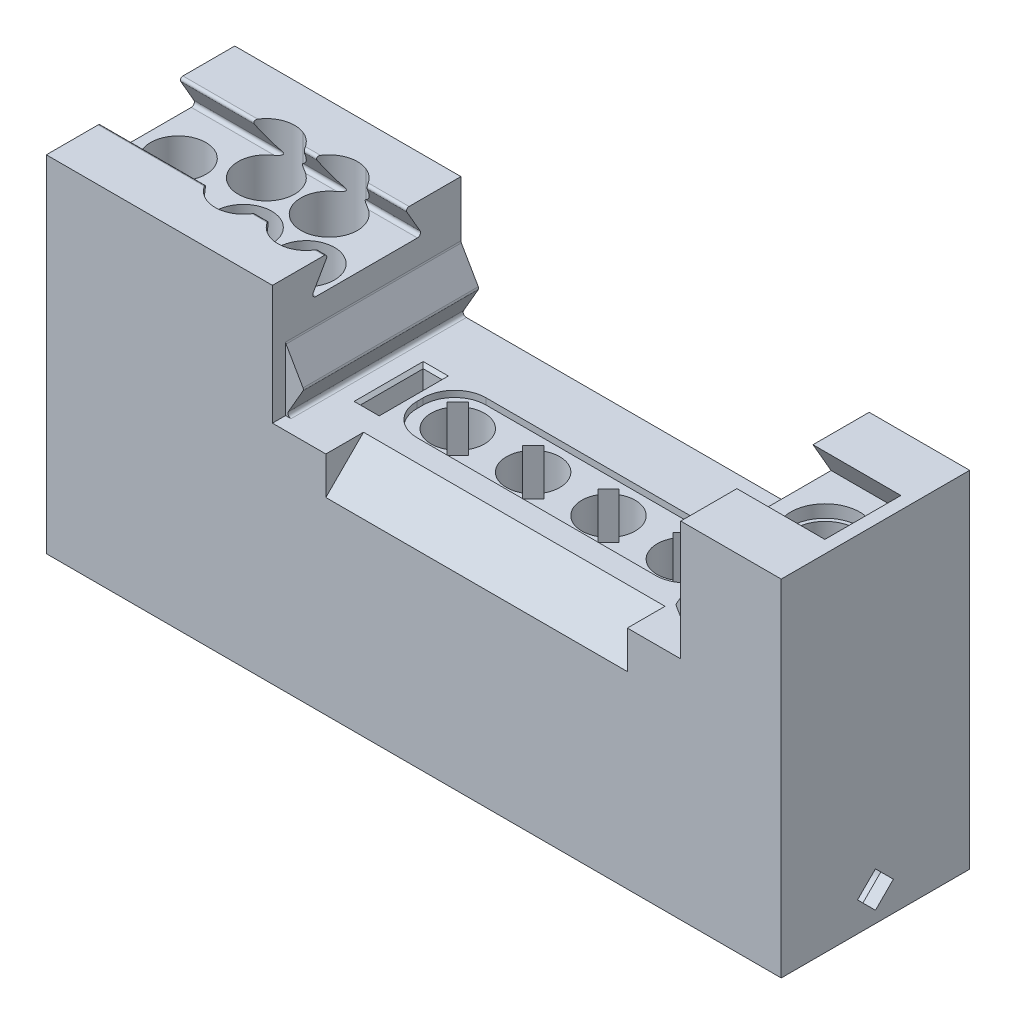
SolidWorks part; units mm, degrees
ref_plane "Front Plane" through (0, 0, 0) normal (0, 0, 1) x (1, 0, 0)
ref_plane "Top Plane" through (0, 0, 0) normal (0, 1, 0) x (1, 0, 0)
ref_plane "Right Plane" through (0, 0, 0) normal (1, 0, 0) x (0, 0, -1)
sketch "Sketch1" plane through (0, 0, 0) normal (0, 1, 0) x (1, 0, 0)
  line L1 (57.5, -15) -> (-57.5, -15)
  line L2 (57.5, -15) -> (57.5, 15)
  line L3 (57.5, 15) -> (-57.5, 15)
  line L4 (-57.5, -15) -> (-57.5, 15)
  line L5 (57.5, -15) -> (-57.5, 15) construction
  line L6 (57.5, 15) -> (-57.5, -15) construction
  point P0 (0, 0)
  dimension "D1" = 30
  dimension "D2" = 115
extrude "Boss-Extrude1" add sketch "Sketch1" along normal mid plane 55
sketch "Sketch2" plane through (0, 0, 0) normal (1, 0, 0) x (0, 0, -1)
  line L0 (0, 27.5) -> (0, 22.5) construction
  line L2 (-15, 27.5) -> (15, 27.5) construction
  line L3 (-6.0566, 27.5) -> (-8.9434, 22.5)
  line L4 (6.0566, 27.5) -> (8.9434, 22.5)
  line L5 (-8.9434, 22.5) -> (8.9434, 22.5)
  line L6 (-8.9434, 22.5) -> (-15, 22.5) construction
  line L7 (-15, 27.5) -> (-15, -27.5) construction
  line L8 (8.9434, 22.5) -> (15, 22.5) construction
  line L9 (-6.0566, 27.5) -> (0, 27.5)
  line L10 (0, 27.5) -> (6.0566, 27.5)
  dimension "D1" = 5
  dimension "D2" = 30
extrude "Cut-Extrude1" cut sketch "Sketch2" against normal through all both and the other way through all
sketch "Sketch5" plane through (0, 22.5, 0) normal (0, 1, 0) x (1, 0, 0)
  line L0 (-51.5, 0) -> (0, 0) construction
  line L1 (-57.5, -8.9434) -> (-57.5, 8.9434) construction
  circle A0 centre (-51.5, 0) radius 4.4
  dimension "D2" = 8.8
  dimension "D1" = 6
extrude "Cut-Extrude3" cut sketch "Sketch5" against normal blind 8
sketch "Sketch3" plane through (0, 22.5, 0) normal (0, 1, 0) x (1, 0, 0)
  line L0 (0, 0) -> (51.5, 0) construction
  line L1 (57.5, -8.9434) -> (57.5, 8.9434) construction
  circle A0 centre (51.5, 0) radius 4.9
  dimension "D1" = 9.8
  dimension "D2" = 6
extrude "Cut-Extrude2" cut sketch "Sketch3" against normal blind 24
sketch "Sketch6" plane through (0, 14.5, 0) normal (0, 1, 0) x (1, 0, 0)
  circle A0 centre (-51.5, 0) radius 3.1
  dimension "D1" = 6.2
extrude "Cut-Extrude4" cut sketch "Sketch6" against normal blind 6
sketch "Sketch7" plane through (0, 22.5, 0) normal (0, 1, 0) x (1, 0, 0)
  circle A0 centre (51.5, 0) radius 5.5
  dimension "D1" = 11
extrude "Cut-Extrude5" cut sketch "Sketch7" against normal blind 2
sketch "Sketch10" plane through (0, 0, 0) normal (0, 0, 1) x (1, 0, 0)
  line L0 (11, 27.5) -> (11, 8.5) construction
  line L1 (-57.5, 27.5) -> (57.5, 27.5) construction
  line L2 (-21.5, 27.5) -> (-21.5, 18.5)
  line L3 (43.5, 27.5) -> (43.5, 18.5)
  line L4 (-21.5, 18.5) -> (-18.6132, 13.5)
  line L5 (43.5, 18.5) -> (40.6132, 13.5)
  line L6 (-18.6132, 13.5) -> (-21.5, 8.5)
  line L7 (40.6132, 13.5) -> (43.5, 8.5)
  line L8 (-21.5, 8.5) -> (43.5, 8.5)
  line L9 (-21.5, 27.5) -> (43.5, 27.5)
  dimension "D1" = 19
  dimension "D2" = 60
  dimension "D3" = 65
  dimension "D4" = 11
  dimension "D5" = 5
extrude "Cut-Extrude7" cut sketch "Sketch10" against normal through all both and the other way through all
fillet "Fillet2" radius 0.4 4 edges at (-39.5, 27.5, 6.0566) (-39.5, 27.5, -6.0566) (40.6132, 13.5, 0) (-18.6132, 13.5, 0)
fillet "Fillet1" radius 0.5 6 edges at (-39.5, 22.5, 8.9434) (-39.5, 22.5, -8.9434) (-21.5, 18.5, 0) (-21.5, 8.5, 0) (43.5, 18.5, 0) (43.5, 8.5, 0)
sketch "Sketch13" plane through (57.5, 0, 0) normal (1, 0, 0) x (0, 0, -1)
  line L1 (-15, 27.5) -> (15, 27.5)
  line L2 (-15, 27.5) -> (-15, -27.5)
  line L3 (-15, -27.5) -> (15, -27.5)
  line L4 (15, 27.5) -> (15, -27.5)
extrude "Boss-Extrude2" add sketch "Sketch13" along normal blind 2
sketch "Sketch16" plane through (-57.5, 0, 0) normal (-1, 0, 0) x (0, 0, 1)
  line L0 (0, -27.5) -> (0, -7.5) construction
  line L9 (-15, -27.5) -> (15, -27.5) construction
  line L10 (-11, -27.5) -> (-11, -12.5) construction
  line L11 (11, -27.5) -> (11, -12.5) construction
  line L12 (-11, -12.5) -> (-11, -7.5)
  line L13 (11, -12.5) -> (11, -7.5)
  line L14 (-11, -7.5) -> (-2, 1.5)
  line L15 (11, -7.5) -> (2, 1.5)
  line L16 (-2, 1.5) -> (2, 1.5)
  line L17 (-11, -12.5) -> (11, -12.5)
  line L18 (-15, 27.5) -> (-15, -27.5) construction
  dimension "D1" = 4
  dimension "D2" = 15
  dimension "D3" = 135
  dimension "D4" = 4
  dimension "D5" = 5
extrude "Cut-Extrude10" cut sketch "Sketch16" against normal blind 35
sketch "Sketch17" plane through (-57.5, 0, 0) normal (-1, 0, 0) x (0, 0, 1)
  line L0 (-15, -27.5) -> (15, -27.5) construction
  line L1 (-11, -12.5) -> (11, -12.5)
  line L2 (-11, -12.5) -> (-11, -27.5)
  line L3 (-11, -27.5) -> (11, -27.5)
  line L4 (11, -12.5) -> (11, -27.5)
  line L5 (11, -12.5) -> (11, -7.5) construction
extrude "Cut-Extrude11" cut sketch "Sketch17" against normal blind 2
fillet "Fillet6" radius 2 4 edges at (-40, -7.5, 11) (-40, 1.5, 2) (-40, 1.5, -2) (-40, -7.5, -11)
sketch "Sketch18" plane through (-57.5, 0, 0) normal (-1, 0, 0) x (0, 0, 1)
  line L21 (-13, -27.5) -> (13, -27.5)
  line L26 (13, -27.5) -> (13, -8.3284)
  line L27 (11.8284, -5.5) -> (4, 2.3284)
  line L28 (1.1716, 3.5) -> (-1.1716, 3.5)
  line L29 (-4, 2.3284) -> (-11.8284, -5.5)
  line L30 (-13, -8.3284) -> (-13, -27.5)
  line L31 (13, -27.5) -> (13, -8.3284)
  line L32 (11.8284, -5.5) -> (4, 2.3284)
  line L33 (1.1716, 3.5) -> (-1.1716, 3.5)
  line L34 (-4, 2.3284) -> (-11.8284, -5.5)
  line L35 (-13, -8.3284) -> (-13, -27.5)
  arc A8 (13, -8.3284) -> (11.8284, -5.5) centre (9, -8.3284) ccw
  arc A9 (4, 2.3284) -> (1.1716, 3.5) centre (1.1716, -0.5) ccw
  arc A10 (-1.1716, 3.5) -> (-4, 2.3284) centre (-1.1716, -0.5) ccw
  arc A11 (-11.8284, -5.5) -> (-13, -8.3284) centre (-9, -8.3284) ccw
  arc A12 (13, -8.3284) -> (11.8284, -5.5) centre (9, -8.3284) ccw
  arc A13 (4, 2.3284) -> (1.1716, 3.5) centre (1.1716, -0.5) ccw
  arc A14 (-1.1716, 3.5) -> (-4, 2.3284) centre (-1.1716, -0.5) ccw
  arc A15 (-11.8284, -5.5) -> (-13, -8.3284) centre (-9, -8.3284) ccw
  dimension "D1" = 2
extrude "Cut-Extrude13" cut sketch "Sketch18" against normal blind 1 from offset 1 offset against normal yes
sketch "Sketch19" plane through (-55.5, 0, 0) normal (-1, 0, 0) x (0, 0, 1)
  line L0 (0, -27.5) -> (0, -12.5) construction
  line L5 (5.6569, -20) -> (0, -14.3431)
  line L6 (5.6569, -20) -> (0, -25.6569)
  line L7 (-13, -27.5) -> (13, -27.5) construction
  line L8 (11, -12.5) -> (-11, -12.5) construction
  line L9 (0, -14.3431) -> (-5.6569, -20)
  line L10 (0, -25.6569) -> (-5.6569, -20)
  line L11 (5.6569, -20) -> (-5.6569, -20) construction
  line L12 (0, -14.3431) -> (0, -25.6569) construction
  line L21 (0, -23.5355) -> (-3.5355, -20) construction
  line L22 (0, -23.5355) -> (3.5355, -20) construction
  line L23 (-3.5355, -20) -> (0, -16.4645) construction
  line L24 (3.5355, -20) -> (0, -16.4645) construction
  line L25 (0, -23.5355) -> (0, -16.4645) construction
  line L26 (-3.5355, -20) -> (3.5355, -20) construction
  point P1 (0, -20)
  point P2 (0, -20)
  point P11 (0, -20)
  dimension "D2" = 8
  dimension "D1" = 5
extrude "Cut-Extrude14" cut sketch "Sketch19" against normal offset from surface (105 mm away) 10 up to face at (59.5, 0, 0)
sketch "Sketch21" plane through (59.5, 0, 0) normal (1, 0, 0) x (0, 0, -1)
  line L0 (0, -25.6569) -> (-5.6569, -20) construction
  line L1 (5.6569, -20) -> (0, -25.6569) construction
  line L2 (0, -25.6569) -> (-5.6569, -20) construction
  line L3 (5.6569, -20) -> (0, -25.6569) construction
  line L20 (5.4801, -19.8232) -> (0, -25.3033) construction
  line L21 (0, -25.3033) -> (-5.4801, -19.8232) construction
  line L22 (0, -25.3033) -> (-2.5, -22.8033) construction
  line L23 (0, -25.3033) -> (2.5, -22.8033) construction
  line L24 (-2.5, -22.8033) -> (0, -20.3033) construction
  line L25 (2.5, -22.8033) -> (0, -20.3033) construction
  circle A0 centre (0, -22.8033) radius 2.5 construction
  circle A1 centre (0, -22.8033) radius 3.75
  dimension "D2" = 5
  dimension "D3" = 7.5
  dimension "D1" = 0.25
extrude "Cut-Extrude15" cut sketch "Sketch21" against normal blind 30 from offset 2 offset against normal yes
sketch "Sketch29" plane through (59.5, 0, 0) normal (1, 0, 0) x (0, 0, -1)
  line L0 (0, -25.3033) -> (-5.4801, -19.8232) construction
  line L1 (2.5, -22.8033) -> (0, -20.3033) construction
  line L2 (-2.5, -22.8033) -> (0, -20.3033) construction
  line L3 (0, -25.3033) -> (-2.5, -22.8033) construction
  line L12 (2.5, -22.8033) -> (0, -20.3033) construction
  line L13 (-2.5, -22.8033) -> (0, -20.3033) construction
  line L14 (0, -25.6569) -> (-2.8536, -22.8033)
  line L15 (5.4801, -19.8232) -> (0, -25.3033) construction
  line L16 (2.5, -22.8033) -> (0, -25.3033) construction
  line L17 (-2.8536, -22.8033) -> (0, -19.9497)
  line L18 (2.8536, -22.8033) -> (0, -19.9497)
  line L19 (2.8536, -22.8033) -> (0, -25.6569)
  dimension "D2" = 0.25
extrude "Cut-Extrude23" cut sketch "Sketch29" against normal up to next
sketch "Sketch23" plane through (0, 0, 15) normal (0, 0, 1) x (1, 0, 0)
  line L0 (-21.5, 18.634) -> (-21.5, 8.5)
  line L1 (-21.5, 8.5) -> (-20.634, 8.5)
  line L2 (-20.634, 8.5) -> (42.634, 8.5)
  line L5 (43.5, 18.634) -> (-21.5, 18.634)
  line L6 (42.634, 8.5) -> (43.5, 8.5)
  line L7 (43.5, 8.5) -> (43.5, 18.634)
extrude "Cut-Extrude17" cut sketch "Sketch23" against normal blind 2.1
sketch "Sketch24" plane through (0, 8.5, 0) normal (0, 1, 0) x (1, 0, 0)
  line L0 (11, 15) -> (11, -15) construction
  line L1 (-20.634, 15) -> (42.634, 15) construction
  line L2 (-21.5, -15) -> (43.5, -15) construction
  line L3 (-7, 0) -> (5, 0) construction
  line L4 (49.5, 0) -> (-55.5, 0) construction
  line L5 (29, 0) -> (17, 0) construction
  line L6 (5, 0) -> (17, 0) construction
  circle A0 centre (-7, 0) radius 4.25
  circle A1 centre (29, 0) radius 4.25
  circle A2 centre (5, 0) radius 4.25
  circle A3 centre (17, 0) radius 4.25
  dimension "D2" = 8.5
  dimension "D1" = 12
extrude "Cut-Extrude18" cut sketch "Sketch24" against normal blind 20
sketch "Sketch22" plane through (0, 8.5, 0) normal (0, 1, 0) x (1, 0, 0)
  line L0 (49.5, 0) -> (-55.5, 0) construction
  line L1 (-14.5, -5) -> (-17.5, -5)
  line L2 (-14.5, -5) -> (-14.5, 5)
  line L3 (-14.5, 5) -> (-17.5, 5)
  line L4 (-17.5, -5) -> (-17.5, 5)
  line L5 (-14.5, -5) -> (-17.5, 5) construction
  line L6 (-14.5, 5) -> (-17.5, -5) construction
  line L7 (-16, 0) -> (0, 0) construction
  point P0 (-16, 0)
  dimension "D1" = 3
  dimension "D2" = 10
  dimension "D3" = 16
extrude "Cut-Extrude16" cut sketch "Sketch22" against normal up to next
sketch "Sketch25" plane through (0, 8.5, 0) normal (0, 1, 0) x (1, 0, 0)
  line L0 (-9.8284, 4.5255) -> (-2.4745, -2.8284)
  line L1 (-9.8284, 4.5255) -> (-11.5255, 2.8284)
  line L2 (-2.4745, -2.8284) -> (-4.1716, -4.5255)
  line L3 (-11.5255, 2.8284) -> (-4.1716, -4.5255)
  line L4 (-9.8284, 4.5255) -> (-4.1716, -4.5255) construction
  line L5 (-2.4745, -2.8284) -> (-11.5255, 2.8284) construction
  line L6 (2.1716, 4.5255) -> (9.5255, -2.8284)
  line L7 (2.1716, 4.5255) -> (0.4745, 2.8284)
  line L8 (9.5255, -2.8284) -> (7.8284, -4.5255)
  line L9 (0.4745, 2.8284) -> (7.8284, -4.5255)
  line L10 (2.1716, 4.5255) -> (7.8284, -4.5255) construction
  line L11 (9.5255, -2.8284) -> (0.4745, 2.8284) construction
  line L12 (14.1716, 4.5255) -> (21.5255, -2.8284)
  line L13 (14.1716, 4.5255) -> (12.4745, 2.8284)
  line L14 (21.5255, -2.8284) -> (19.8284, -4.5255)
  line L15 (12.4745, 2.8284) -> (19.8284, -4.5255)
  line L16 (14.1716, 4.5255) -> (19.8284, -4.5255) construction
  line L17 (21.5255, -2.8284) -> (12.4745, 2.8284) construction
  line L18 (26.1716, 4.5255) -> (33.5255, -2.8284)
  line L19 (26.1716, 4.5255) -> (24.4745, 2.8284)
  line L20 (33.5255, -2.8284) -> (31.8284, -4.5255)
  line L21 (24.4745, 2.8284) -> (31.8284, -4.5255)
  line L22 (26.1716, 4.5255) -> (31.8284, -4.5255) construction
  line L23 (33.5255, -2.8284) -> (24.4745, 2.8284) construction
  line L24 (-20.634, 15) -> (42.634, 15) construction
  circle A0 centre (-7, 0) radius 4.25 construction
  circle A2 centre (17, 0) radius 4.25 construction
  circle A3 centre (29, 0) radius 4.25 construction
  circle A5 centre (5, 0) radius 4.25 construction
  point P0 (-7, 0)
  point P1 (-7, 0)
  point P2 (5, 0)
  point P3 (17, 0)
  point P8 (29, 0)
  point P24 (0, 0)
  point P25 (0, 0)
  point P30 (-1.431, 0.1234)
  point P33 (17, 0)
  point P34 (29, 0)
  point P35 (-17.1147, 4.6522)
  dimension "D1" = 10.4
  dimension "D2" = 2.4
  dimension "D3" = 45
extrude "Cut-Extrude19" cut sketch "Sketch25" against normal up to surface (20 mm away) up to face at (-7, -11.5, 4.25)
sketch "Sketch26" plane through (0, 8.5, 0) normal (0, 1, 0) x (1, 0, 0)
  line L0 (49.5, 0) -> (-14.5, 0) construction
  line L1 (35, -5.5) -> (-13, -5.5)
  line L2 (35, -5.5) -> (35, 5.5)
  line L3 (35, 5.5) -> (-13, 5.5)
  line L4 (-13, -5.5) -> (-13, 5.5)
  line L5 (35, -5.5) -> (-13, 5.5) construction
  line L6 (35, 5.5) -> (-13, -5.5) construction
  line L7 (-20.634, 15) -> (42.634, 15) construction
  point P0 (11, 0)
  point P10 (11, 15)
  dimension "D1" = 48
  dimension "D2" = 11
extrude "Cut-Extrude20" cut sketch "Sketch26" against normal blind 1
fillet "Fillet7" radius 5 4 edges at (35, 8, 5.5) (35, 8, -5.5) (-13, 8, 5.5) (-13, 8, -5.5)
ref_plane "Plane1" through (11, 0, 0) normal (1, 0, 0) x (0, 0, -1)
sketch "Sketch27" plane through (11, 0, 0) normal (1, 0, 0) x (0, 0, -1)
  line L0 (-15, 8.5) -> (-9, 8.5)
  line L1 (-12.9, 8.5) -> (15, 8.5) construction
  line L2 (-9, 8.5) -> (-15, 2.5)
  line L3 (-15, 27.5) -> (-15, -27.5) construction
  line L4 (-15, 2.5) -> (-15, 8.5)
  dimension "D1" = 6
extrude "Cut-Extrude21" cut sketch "Sketch27" against normal blind 24 and the other way blind 24
chamfer "Chamfer1" distance 0.5 angle 45 4 edges at (-16, 8.5, 5) (-17.5, 8.5, 0) (-14.5, 8.5, 0) (-16, 8.5, -5)
sketch "Sketch28" plane through (0, 22.5, 0) normal (0, 1, 0) x (1, 0, 0)
  line L7 (-41.8, 4.3301) -> (-31.8, 4.3301) construction
  line L8 (-36.8, -4.3301) -> (-26.8, -4.3301) construction
  line L9 (-36.8, 4.3301) -> (-36.8, -4.3301) construction
  line L10 (-31.8, 4.3301) -> (-36.8, -4.3301) construction
  line L11 (-47.1, 0) -> (-21.5, 0) construction
  line L12 (-21.5, -8.0774) -> (-21.5, 8.0774) construction
  circle A3 centre (-41.8, 4.3301) radius 4.5
  circle A4 centre (-36.8, -4.3301) radius 4.5
  circle A5 centre (-31.8, 4.3301) radius 4.5
  circle A6 centre (-26.8, -4.3301) radius 4.5
  circle A7 centre (-51.5, 0) radius 4.4 construction
  point P10 (-34.3, 0)
  point P12 (-34.3, 0)
  dimension "D2" = 10
  dimension "D1" = 9
extrude "Cut-Extrude22" cut sketch "Sketch28" against normal blind 17 and the other way up to next
